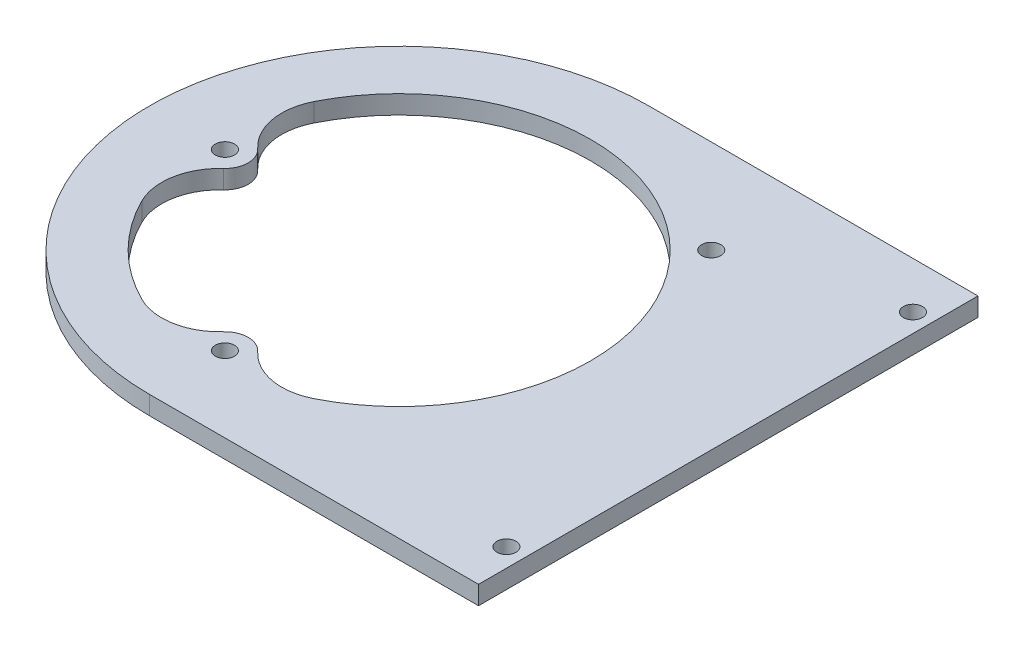
SolidWorks part; units mm, degrees
ref_plane "Front Plane" through (0, 0, 0) normal (0, 0, 1) x (1, 0, 0)
ref_plane "Top Plane" through (0, 0, 0) normal (0, 1, 0) x (1, 0, 0)
ref_plane "Right Plane" through (0, 0, 0) normal (1, 0, 0) x (0, 0, -1)
sketch "Sketch1" plane through (0, 0, 0) normal (0, 1, 0) x (1, 0, 0)
  line L0 (0, 0) -> (30, 0) construction
  line L1 (0, 0) -> (0, -30) construction
  line L2 (0, 0) -> (26.8701, 26.8701) construction
  line L3 (-4, -32.7567) -> (-4, -30)
  line L4 (4, -30) -> (4, -32.7567)
  line L5 (32.7567, 4) -> (30, 4) construction
  line L6 (32.7567, -4) -> (30, -4) construction
  line L7 (0, -43) -> (56.67, -43)
  line L8 (56.67, -43) -> (56.67, 43)
  line L9 (56.67, 43) -> (0, 43)
  line L10 (53.47, 35) -> (56.67, 35) construction
  line L11 (-32.7567, -4) -> (-30, -4)
  line L12 (-32.7567, 4) -> (-30, 4)
  circle A0 centre (0, 0) radius 25 construction
  circle A2 centre (26.8701, 26.8701) radius 1.65
  circle A3 centre (30, 0) radius 1.65 construction
  circle A4 centre (0, -30) radius 1.65
  arc A5 (32.7567, 4) -> (-4, -32.7567) centre (0, 0) ccw construction
  arc A6 (-4, -30) -> (4, -30) centre (0, -30) cw
  arc A7 (4, -32.7567) -> (32.7567, -4) centre (0, 0) ccw
  arc A8 (30, 4) -> (30, -4) centre (30, 0) ccw construction
  arc A9 (0, 43) -> (0, -43) centre (0, 0) ccw
  circle A10 centre (53.47, 35) radius 1.65
  circle A12 centre (53.47, -35) radius 1.65
  circle A13 centre (-30, 0) radius 1.65
  arc A14 (-30, 4) -> (-30, -4) centre (-30, 0) cw
  arc A15 (32.7567, 4) -> (-32.7567, 4) centre (0, 0) ccw
  arc A16 (-4, -32.7567) -> (-32.7567, -4) centre (0, 0) cw
  arc A17 (32.7567, 4) -> (32.7567, -4) centre (0, 0) cw
  point P35 (0, 0)
  dimension "D1" = 50
  dimension "D2" = 30
  dimension "D4" = 3.3
  dimension "D6" = 33
  dimension "D7" = 4
  dimension "D9" = 43
  dimension "D3" = 45
  dimension "D5" = 38
  dimension "D8" = 56.67
  dimension "D10" = 3.2
  dimension "D11" = 35
extrude "Boss-Extrude1" add sketch "Sketch1" along normal blind 3.2
fillet "Fillet1" radius 10 4 edges at (4, 1.6, 32.7567) (-32.7567, 1.6, -4) (-32.7567, 1.6, 4) (-4, 1.6, 32.7567)
